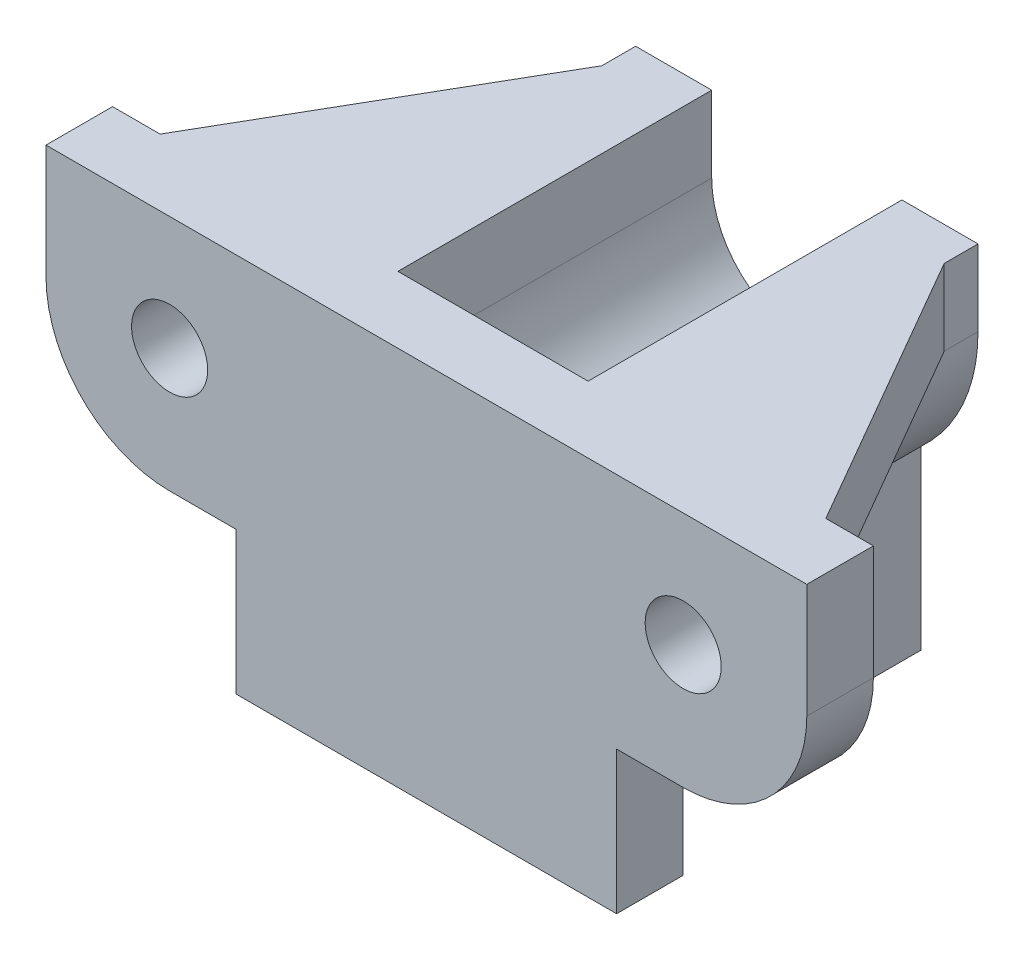
SolidWorks part; units mm, degrees
ref_plane "前视基准面" through (0, 0, 0) normal (0, 0, 1) x (1, 0, 0)
ref_plane "上视基准面" through (0, 0, 0) normal (0, 1, 0) x (1, 0, 0)
ref_plane "右视基准面" through (0, 0, 0) normal (1, 0, 0) x (0, 0, -1)
sketch "草图1" plane through (0, 0, 0) normal (0, 0, 1) x (1, 0, 0)
  line L0 (-40, 0) -> (40, 0)
  line L1 (40, 0) -> (40, -12)
  line L2 (27, -25) -> (20, -25)
  line L3 (20, -25) -> (20, -40)
  line L4 (20, -40) -> (-20, -40)
  line L5 (-20, -40) -> (-20, -25)
  line L6 (-20, -25) -> (-27, -25)
  line L7 (-40, -12) -> (-40, 0)
  line L8 (0, 23.5658) -> (0, -70.3125) construction
  arc A0 (40, -12) -> (27, -25) centre (27, -12) cw
  arc A1 (-27, -25) -> (-40, -12) centre (-27, -12) cw
  circle A2 centre (-27, -12) radius 4
  circle A3 centre (27, -12) radius 4
  point P17 (-40, -25)
  dimension "D5" = 13
  dimension "D6" = 8
  dimension "D1" = 80
  dimension "D2" = 40
  dimension "D3" = 25
  dimension "D4" = 40
extrude "凸台-拉伸1" add sketch "草图1" against normal blind 7
sketch "草图2" plane through (0, 0, -7) normal (0, 0, -1) x (-1, 0, 0)
  line L0 (0, 11.439) -> (0, -44.5419) construction
  line L1 (-10, 0) -> (-10, -8)
  line L2 (-40, 0) -> (40, 0) construction
  line L3 (-18, 0) -> (-18, -8)
  line L4 (18, 0) -> (18, -8)
  line L5 (10, 0) -> (10, -8)
  line L6 (-18, 0) -> (-10, 0)
  line L7 (10, 0) -> (18, 0)
  arc A0 (-10, -8) -> (10, -8) centre (0, -8) ccw
  arc A1 (-18, -8) -> (18, -8) centre (0, -8) ccw
  dimension "D1" = 20
  dimension "D2" = 36
  dimension "D3" = 8
  dimension "D4" = 8
extrude "凸台-拉伸2" add sketch "草图2" along normal blind 33
sketch "草图3" plane through (0, 0, 0) normal (0, 1, 0) x (1, 0, 0)
  line L0 (0, 51.3538) -> (0, -2.919) construction
  line L1 (40, 7) -> (18, 7) construction
  line L2 (18, 40) -> (18, 7) construction
  line L3 (18, 36.4449) -> (35, 7)
  line L4 (-18, 36.4449) -> (-35, 7)
  line L5 (-18, 36.4449) -> (-18, 7)
  line L6 (-18, 7) -> (-35, 7)
  line L7 (18, 36.4449) -> (18, 7)
  line L8 (18, 7) -> (35, 7)
  point P3 (35, 7)
  point P4 (-18, 36.4449)
  point P7 (-35, 7)
  point P9 (18, 36.4449)
  dimension "D1" = 70
  dimension "D2" = 30
extrude "凸台-拉伸3" add sketch "草图3" against normal blind 8
sketch "草图4" plane through (0, -40, 0) normal (0, -1, 0) x (1, 0, 0)
  line L0 (0, -50.587) -> (0, 3.6006) construction
  line L1 (12, -40) -> (12, -31)
  line L2 (-18, -40) -> (18, -40) construction
  line L5 (-12, -40) -> (-12, -31)
  line L6 (12, -40) -> (-12, -40)
  line L7 (12, -31) -> (-12, -31) construction
  line L8 (3, -7) -> (3, -19.381)
  line L9 (-20, -7) -> (20, -7) construction
  line L10 (-3, -7) -> (-3, -19.381)
  line L11 (3, -7) -> (-3, -7)
  arc A1 (12, -31) -> (3, -19.381) centre (0, -31) ccw
  arc A2 (-3, -19.381) -> (-12, -31) centre (0, -31) ccw
  dimension "D1" = 24
  dimension "D2" = 9
  dimension "D3" = 6
extrude "凸台-拉伸4" add sketch "草图4" against normal up to surface (18.5836 mm away)
sketch "草图5" plane through (0, -40, 0) normal (0, -1, 0) x (1, 0, 0)
  line L0 (0, -49.1386) -> (0, 4.8786) construction
  line L1 (6, -40) -> (6, -31)
  line L2 (-12, -40) -> (12, -40) construction
  line L3 (-6, -40) -> (-6, -31)
  line L4 (6, -31) -> (-6, -31) construction
  line L5 (6, -40) -> (-6, -40)
  arc A0 (6, -31) -> (-6, -31) centre (0, -31) ccw
  dimension "D1" = 9
  dimension "D2" = 12
extrude "切除-拉伸1" cut sketch "草图5" against normal through all
